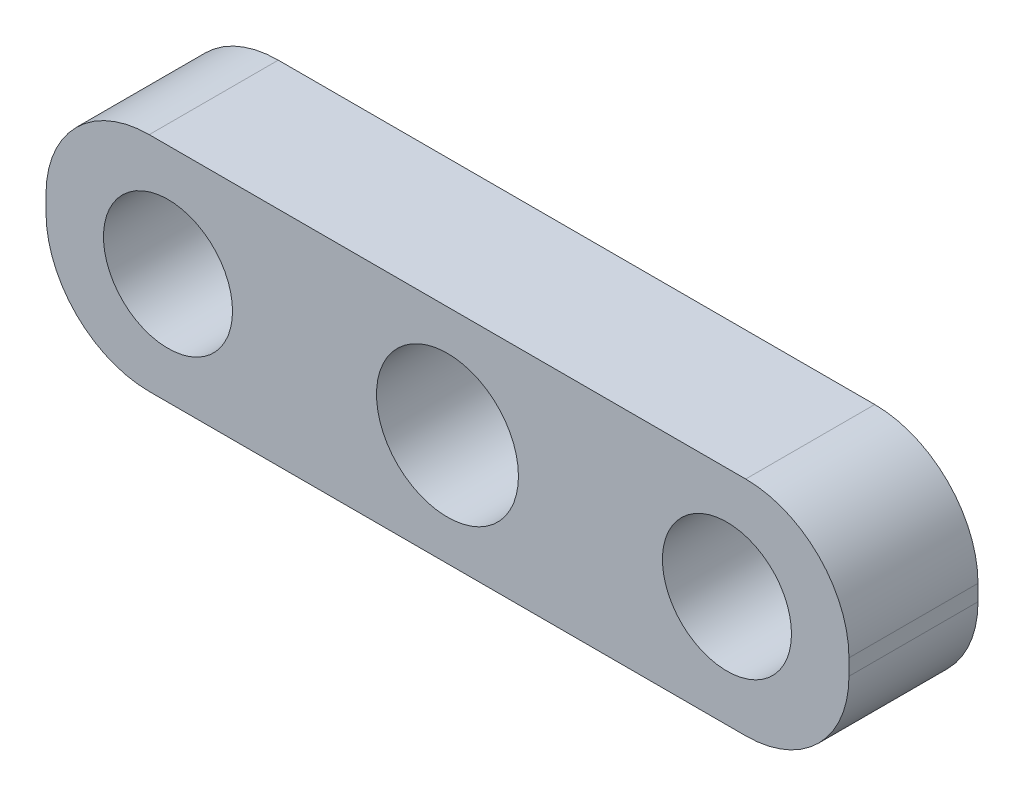
SolidWorks part; units mm, degrees
ref_plane "Front Plane" through (0, 0, 0) normal (0, 0, 1) x (1, 0, 0)
ref_plane "Top Plane" through (0, 0, 0) normal (0, 1, 0) x (1, 0, 0)
ref_plane "Right Plane" through (0, 0, 0) normal (1, 0, 0) x (0, 0, -1)
sketch "Sketch1" plane through (0, 0, 0) normal (0, 0, 1) x (1, 0, 0)
  line L0 (8.4367, -20.4263) -> (8.4367, -17.0625) construction
  line L1 (10.8285, -17.0625) -> (8.4367, -17.0625) construction
  line L2 (17.157, -13.0542) -> (17.157, -7.0708) construction
  line L3 (8.4367, -3.4838) -> (8.4367, 3.4838) construction
  line L4 (17.157, 7.0708) -> (17.157, 13.0542) construction
  line L5 (8.4367, 17.0625) -> (10.8285, 17.0625) construction
  line L6 (8.4367, 17.0625) -> (8.4367, 20.4263) construction
  line L7 (-8.4367, 17.0625) -> (-8.4367, 20.4263) construction
  line L8 (-10.8285, 17.0625) -> (-8.4367, 17.0625) construction
  line L9 (-17.157, 7.0708) -> (-17.157, 13.0542) construction
  line L10 (-8.4367, -3.4838) -> (-8.4367, 3.4838) construction
  line L11 (-17.157, -13.0542) -> (-17.157, -7.0708) construction
  line L12 (-8.4367, -17.0625) -> (-10.8285, -17.0625) construction
  line L13 (-8.4367, -20.4263) -> (-8.4367, -17.0625) construction
  line L14 (-6.9367, -14.3718) -> (-6.9367, -5.7532) construction
  line L15 (-15.5553, -14.3718) -> (-6.9367, -14.3718) construction
  line L16 (-15.5553, -14.3718) -> (-15.5553, -5.7532) construction
  line L17 (-15.5553, -5.7532) -> (-6.9367, -5.7532) construction
  line L18 (6.9367, 14.3718) -> (6.9367, 5.7532) construction
  line L19 (15.5553, 14.3718) -> (6.9367, 14.3718) construction
  line L20 (15.5553, 14.3718) -> (15.5553, 5.7532) construction
  line L21 (15.5553, 5.7532) -> (6.9367, 5.7532) construction
  line L22 (-4.5, 14.5625) -> (-4.5, 5.5625) construction
  line L23 (4.5, 14.5625) -> (-4.5, 14.5625) construction
  line L24 (4.5, 14.5625) -> (4.5, 5.5625) construction
  line L25 (4.5, 5.5625) -> (-4.5, 5.5625) construction
  line L26 (-4.5, -5.5625) -> (-4.5, -14.5625) construction
  line L27 (4.5, -5.5625) -> (-4.5, -5.5625) construction
  line L28 (4.5, -5.5625) -> (4.5, -14.5625) construction
  line L29 (4.5, -14.5625) -> (-4.5, -14.5625) construction
  line L30 (15.5553, -14.3718) -> (6.9367, -14.3718) construction
  line L31 (6.9367, -14.3718) -> (6.9367, -5.7532) construction
  line L32 (15.5553, -5.7532) -> (6.9367, -5.7532) construction
  line L33 (15.5553, -14.3718) -> (15.5553, -5.7532) construction
  line L34 (-15.5553, 14.3718) -> (-6.9367, 14.3718) construction
  line L35 (0, 14.3718) -> (0, 5.7532)
  line L36 (-15.5553, 5.7532) -> (15.5553, 5.7532) construction
  line L37 (-15.5553, 14.3718) -> (-15.5553, 5.7532) construction
  line L39 (-15.5553, 5.7532) -> (15.5553, 5.7532)
  line L40 (-15.5553, 5.7532) -> (-15.5553, 14.3718)
  line L41 (-15.5553, 14.3718) -> (15.5553, 14.3718)
  line L42 (15.5553, 5.7532) -> (15.5553, 14.3718)
  arc A0 (-8.4367, -20.4263) -> (8.4367, -20.4263) centre (0, 0) ccw construction
  arc A1 (10.8285, -17.0625) -> (17.157, -13.0542) centre (10.8285, -10.0625) ccw construction
  arc A2 (17.157, -7.0708) -> (8.4367, -3.4838) centre (10.8285, -10.0625) ccw construction
  arc A3 (8.4367, 3.4838) -> (17.157, 7.0708) centre (10.8285, 10.0625) ccw construction
  arc A4 (17.157, 13.0542) -> (10.8285, 17.0625) centre (10.8285, 10.0625) ccw construction
  arc A5 (8.4367, 20.4263) -> (-8.4367, 20.4263) centre (0, 0) ccw construction
  arc A6 (-10.8285, 17.0625) -> (-17.157, 13.0542) centre (-10.8285, 10.0625) ccw construction
  arc A7 (-17.157, 7.0708) -> (-8.4367, 3.4838) centre (-10.8285, 10.0625) ccw construction
  arc A8 (-8.4367, -3.4838) -> (-17.157, -7.0708) centre (-10.8285, -10.0625) ccw construction
  arc A9 (-17.157, -13.0542) -> (-10.8285, -17.0625) centre (-10.8285, -10.0625) ccw construction
  circle A10 centre (0, 0) radius 4.9125 construction
  circle A11 centre (10.8285, -10.0625) radius 2.5 construction
  circle A12 centre (-10.8285, -10.0625) radius 2.5 construction
  circle A13 centre (-10.8285, 10.0625) radius 2.5 construction
  circle A14 centre (10.8285, 10.0625) radius 2.5 construction
  circle A15 centre (-10.8285, 10.0625) radius 2.5
  circle A16 centre (10.8285, 10.0625) radius 2.5
  point P63 (0, 0)
extrude "Boss-Extrude1" add sketch "Sketch1" along normal blind 5 contours L41 L40 L39 L35 A15 | L39 L42 L41 L35 A16
sketch "Sketch2" plane through (0, 0, 5) normal (0, 0, 1) x (1, 0, 0)
  line L0 (-8.3285, 10.0625) -> (8.3285, 10.0625) construction
  circle A0 centre (-10.8285, 10.0625) radius 2.5 construction
  circle A1 centre (10.8285, 10.0625) radius 2.5 construction
  circle A2 centre (0, 10.0625) radius 2.75
  dimension "D1" = 5.5
extrude "Cut-Extrude1" cut sketch "Sketch2" against normal through all
fillet "Fillet1" radius 4 4 edges at (-15.5553, 14.3718, 2.5) (15.5553, 14.3718, 2.5) (15.5553, 5.7532, 2.5) (-15.5553, 5.7532, 2.5)
